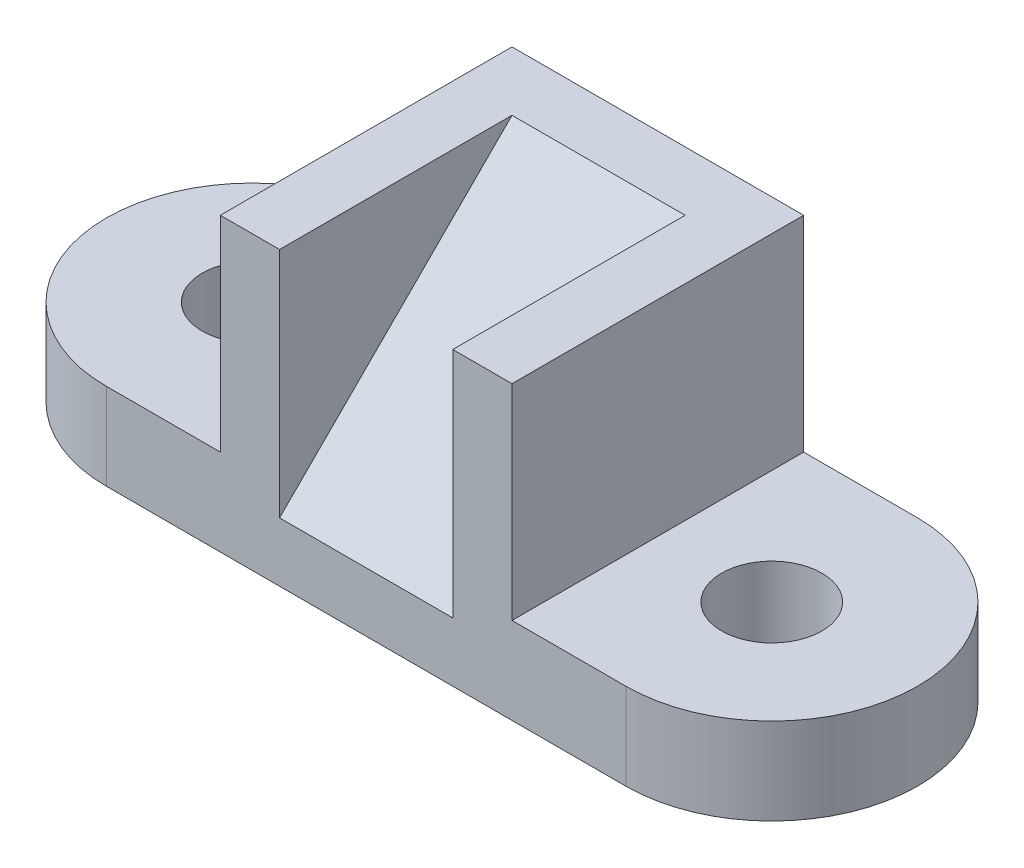
SolidWorks part; units mm, degrees
ref_plane "Front Plane" through (0, 0, 0) normal (0, 0, 1) x (1, 0, 0)
ref_plane "Top Plane" through (0, 0, 0) normal (0, 1, 0) x (1, 0, 0)
ref_plane "Right Plane" through (0, 0, 0) normal (1, 0, 0) x (0, 0, -1)
sketch "Sketch1" plane through (0, 0, 0) normal (0, 1, 0) x (1, 0, 0)
  line L1 (-57, -32) -> (57, -32)
  line L3 (-57, 32) -> (57, 32)
  arc A0 (-57, 32) -> (-57, -32) centre (-57, 0) ccw
  arc A1 (57, -32) -> (57, 32) centre (57, 0) ccw
  circle A2 centre (-57, 0) radius 11
  circle A3 centre (57, 0) radius 11
  point P0 (0, 0)
  dimension "D1" = 32
  dimension "D3" = 22
  dimension "D4" = 22
  dimension "D2" = 114
extrude "Boss-Extrude1" add sketch "Sketch1" along normal blind 13
sketch "Sketch2" plane through (0, 13, 0) normal (0, 1, 0) x (1, 0, 0)
  line L1 (-19, -32) -> (19, -32)
  line L2 (-19, -32) -> (-19, 19)
  line L4 (19, -32) -> (19, 19)
  line L5 (-19, -32) -> (11.2813, 19) construction
  line L6 (-11.2812, 19) -> (19, -32) construction
  line L7 (-19, 19) -> (19, 19)
  point P0 (0, 0)
extrude "Boss-Extrude2" add sketch "Sketch2" along normal blind 51
sketch "Sketch3" plane through (-19, 0, 0) normal (-1, 0, 0) x (0, 0, 1)
  line L0 (32, 64) -> (32, 13)
  line L1 (32, 13) -> (-19, 64)
  line L2 (-19, 64) -> (32, 64)
extrude "Cut-Extrude1" cut sketch "Sketch3" against normal through all
sketch "Sketch4" plane through (0, 13, 0) normal (0, 1, 0) x (1, 0, 0)
  line L6 (-19, -32) -> (-19, 19)
  line L7 (-19, 19) -> (19, 19)
  line L8 (19, 19) -> (19, -32)
  line L9 (19, -32) -> (57, -32)
  line L10 (57, 32) -> (-57, 32)
  line L11 (-57, -32) -> (-19, -32)
  line L12 (-19, -32) -> (-19, 19)
  line L13 (-19, 19) -> (19, 19)
  line L14 (19, 19) -> (19, -32)
  line L15 (19, -32) -> (57, -32)
  line L16 (57, 32) -> (-57, 32)
  line L17 (-57, -32) -> (-19, -32)
  circle A0 centre (-57, 0) radius 11 construction
  circle A1 centre (-57, 0) radius 11
  arc A2 (57, -32) -> (57, 32) centre (57, 0) ccw
  arc A3 (-57, 32) -> (-57, -32) centre (-57, 0) ccw
  arc A4 (57, -32) -> (57, 32) centre (57, 0) ccw
  arc A5 (-57, 32) -> (-57, -32) centre (-57, 0) ccw
  circle A6 centre (57, 0) radius 11 construction
  circle A7 centre (57, 0) radius 11
  dimension "D1" = 0
extrude "Boss-Extrude3" add sketch "Sketch4" along normal blind 6
sketch "Sketch5" plane through (0, 19, 0) normal (0, 1, 0) x (1, 0, 0)
  line L0 (57, 32) -> (-57, 32) construction
  line L1 (-32, -32) -> (-19, -32)
  line L2 (-32, -32) -> (-32, 32)
  line L3 (-32, 32) -> (32, 32)
  line L4 (32, -32) -> (32, 32)
  line L5 (-32, -32) -> (32, 32) construction
  line L6 (-32, 32) -> (32, -32) construction
  line L7 (19, 19) -> (19, -26) construction
  line L8 (19, -26) -> (19, -32) construction
  line L9 (-19, -26) -> (-19, -32) construction
  line L10 (-19, -26) -> (-19, 19) construction
  line L11 (-19, 19) -> (19, 19) construction
  line L12 (19, 19) -> (19, -26)
  line L13 (19, -26) -> (19, -32)
  line L14 (-19, -26) -> (-19, -32)
  line L15 (-19, -26) -> (-19, 19)
  line L16 (-19, 19) -> (19, 19)
  line L17 (19, -32) -> (32, -32)
  point P0 (0, 0)
  dimension "D1" = 64
extrude "Boss-Extrude4" add sketch "Sketch5" along normal blind 45
